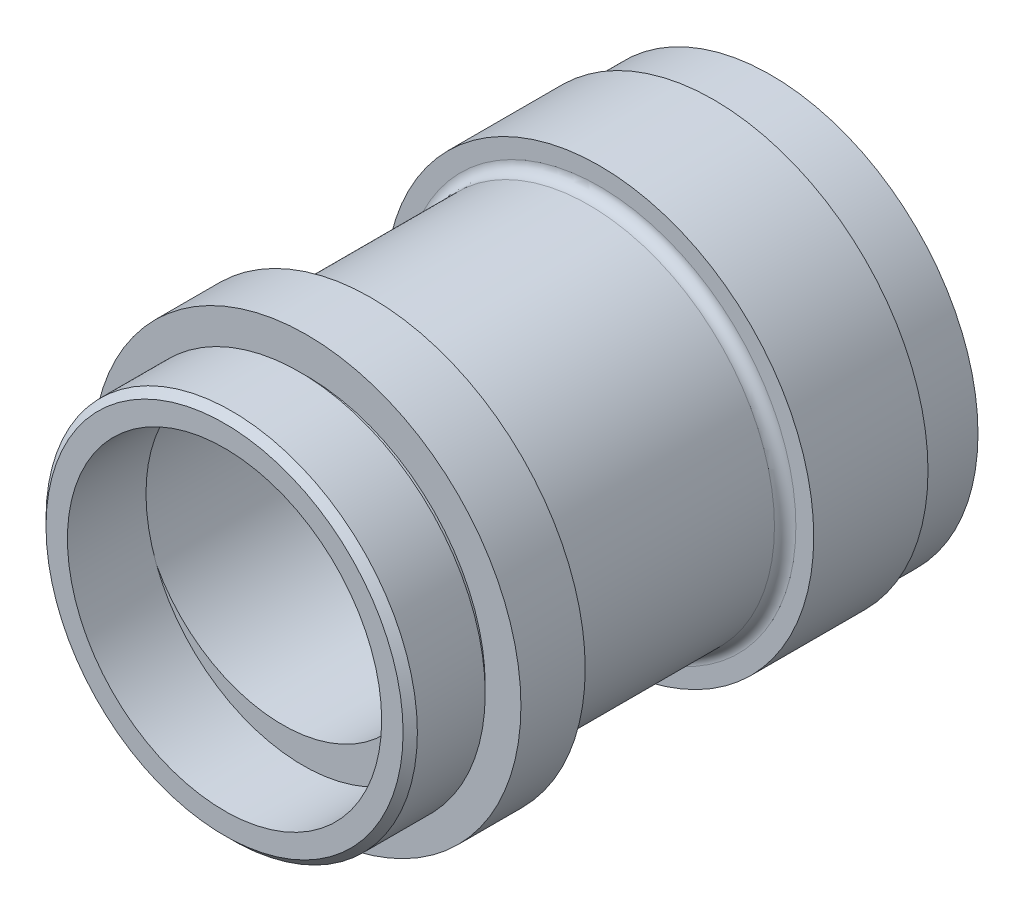
SolidWorks part; units mm, degrees
ref_plane "Plan de face" through (0, 0, 0) normal (0, 0, 1) x (1, 0, 0)
ref_plane "Plan de dessus" through (0, 0, 0) normal (0, 1, 0) x (1, 0, 0)
ref_plane "Plan de droite" through (0, 0, 0) normal (1, 0, 0) x (0, 0, -1)
sketch "Sketch1" plane through (0, 0, 0) normal (0, 0, 1) x (1, 0, 0)
  circle A0 centre (0, 0) radius 14.5
  dimension "D1" = 29
extrude "Boss-Extrude1" add sketch "Sketch1" along normal blind 4
sketch "Sketch2" plane through (0, 0, 4) normal (0, 0, 1) x (1, 0, 0)
  circle A0 centre (0, 0) radius 15
  dimension "D1" = 30
extrude "Boss-Extrude2" add sketch "Sketch2" along normal blind 8
sketch "Sketch3" plane through (0, 0, 12) normal (0, 0, 1) x (1, 0, 0)
  circle A0 centre (0, 0) radius 13
  dimension "D1" = 26
extrude "Boss-Extrude3" add sketch "Sketch3" along normal blind 16
sketch "Sketch4" plane through (0, 0, 28) normal (0, 0, 1) x (1, 0, 0)
  circle A0 centre (0, 0) radius 15
  dimension "D1" = 30
extrude "Boss-Extrude4" add sketch "Sketch4" along normal blind 4.5
sketch "Sketch5" plane through (0, 0, 32.5) normal (0, 0, 1) x (1, 0, 0)
  circle A0 centre (0, 0) radius 12.5
  dimension "D1" = 25
extrude "Boss-Extrude5" add sketch "Sketch5" along normal blind 0.5
sketch "Sketch6" plane through (0, 0, 33) normal (0, 0, 1) x (1, 0, 0)
  circle A0 centre (0, 0) radius 13
  dimension "D1" = 26
extrude "Boss-Extrude6" add sketch "Sketch6" along normal blind 5.25
cosmetic thread "Cosmetic Thread1" parameters "D2"=25
sketch "Sketch7" plane through (0, 0, 38.25) normal (0, 0, 1) x (1, 0, 0)
  circle A0 centre (0, 0) radius 11
  dimension "D1" = 22
extrude "Cut-Extrude1" cut sketch "Sketch7" against normal blind 5.5
sketch "Sketch8" plane through (0, 0, 32.75) normal (0, 0, 1) x (1, 0, 0)
  circle A0 centre (-1.44, 0.75) radius 10
  circle A1 centre (0, 0) radius 15 construction
  dimension "D1" = 20
  dimension "D2" = 0.75
  dimension "D3" = 1.44
other "AlignGroup1"
extrude "Cut-Extrude2" cut sketch "Sketch8" against normal blind 32.75 contours A0
fillet "Fillet1" radius 0.75 2 edges at (13, 0, 12) (13, 0, 28)
sketch "Sketch13" plane through (0, 0, 0) normal (0, 1, 0) x (1, 0, 0)
  line L0 (0, 0) -> (0, -20) construction
  point P2 (0, -20)
  point P7 (0, -20)
  dimension "D1" = 20
chamfer "Chamfer1" distance 0.5 angle 45 1 edges at (13, 0, 38.25)
hole_wizard "Ø2.0 (2) Diameter Hole2" positions "Sketch13" profile "Sketch11" hole size "Ø2.0" standard "ISO"
sketch "Sketch11" plane through (0, 0, 20) normal (1, 0, 0) x (0, 0, 1)
  line L0 (0, 0) -> (0, 15)
  line L1 (0, 15) -> (1, 15)
  line L2 (1, 15) -> (1, 0)
  line L5 (1, 0) -> (0, 0)
  line L11 (0, -6.35) -> (0, 107.95) construction
  dimension "Thru Hole Dia." = 2
  dimension "Thru Hole Depth" = 15
